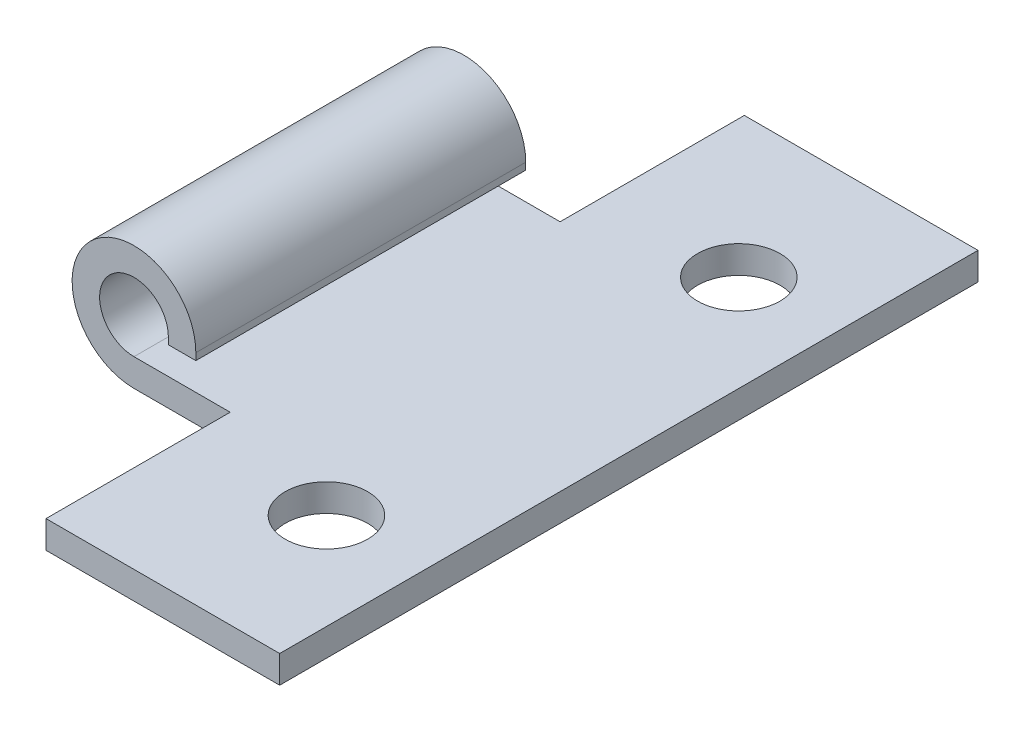
SolidWorks part; units mm, degrees
ref_plane "Alzado" through (0, 0, 0) normal (0, 0, 1) x (1, 0, 0)
ref_plane "Planta" through (0, 0, 0) normal (0, 1, 0) x (1, 0, 0)
ref_plane "Vista lateral" through (0, 0, 0) normal (1, 0, 0) x (0, 0, -1)
sketch "Croquis1" plane through (0, 0, 0) normal (0, 0, 1) x (1, 0, 0)
  line L8 (0, -2.25) -> (12, -2.25)
  line L9 (12, -2.25) -> (12, -1.25)
  line L10 (12, -1.25) -> (1.8708, -1.25)
  line L11 (1.25, -0.25) -> (2.2361, -0.25)
  line L12 (1.25, 0) -> (1.25, -0.25)
  line L13 (2.25, 0) -> (2.25, -0.25)
  line L14 (2.25, -0.25) -> (2.2361, -0.25)
  line L15 (1.8708, -1.25) -> (0, -1.25)
  arc A2 (1.25, 0) -> (0, -1.25) centre (0, 0) ccw
  arc A3 (2.25, 0) -> (0, -2.25) centre (0, 0) ccw
  dimension "D2" = 2.5
  dimension "D3" = 1
  dimension "D1" = 12
  dimension "D4" = 1
  dimension "D5" = 1
extrude "Saliente-Extruir1" add sketch "Croquis1" along normal blind 25.4
sketch "Croquis4" plane through (0, -2.25, 0) normal (0, -1, 0) x (1, 0, 0)
  line L0 (-2.25, 25.4) -> (-2.25, 0) construction
  line L1 (-2.25, 18.7) -> (3.5, 18.7)
  line L3 (-2.25, 6.7) -> (3.5, 6.7)
  line L4 (3.5, 18.7) -> (3.5, 6.7) construction
  line L5 (8.5, 5.2) -> (8.5, 20.2) construction
  line L6 (12, 12.7) -> (3.5, 12.7) construction
  line L7 (12, 25.4) -> (12, 0) construction
  line L8 (0, 25.4) -> (12, 25.4) construction
  line L9 (3.5, 18.7) -> (3.5, 25.4)
  line L10 (3.5, 25.4) -> (-2.25, 25.4)
  line L11 (-2.25, 25.4) -> (-2.25, 18.7)
  line L12 (3.5, 6.7) -> (3.5, 0)
  line L13 (0, 0) -> (12, 0) construction
  line L14 (3.5, 0) -> (-2.25, 0)
  line L15 (-2.25, 0) -> (-2.25, 6.7)
  circle A0 centre (8.5, 20.2) radius 1.5
  circle A1 centre (8.5, 5.2) radius 1.5
  point P14 (8.5, 12.7)
  dimension "D3" = 3
  dimension "D1" = 8.5
  dimension "D2" = 12
  dimension "D4" = 15
  dimension "D5" = 3.5
extrude "Cortar-Extruir3" cut sketch "Croquis4" against normal through all
